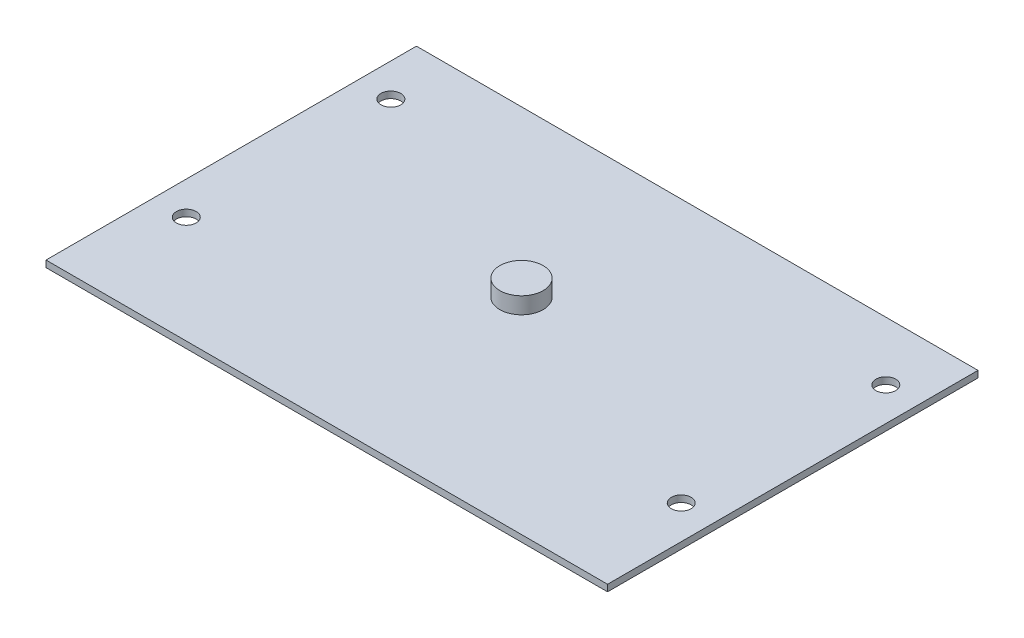
SolidWorks part; units mm, degrees
ref_plane "Front Plane" through (0, 0, 0) normal (0, 0, 1) x (1, 0, 0)
ref_plane "Top Plane" through (0, 0, 0) normal (0, 1, 0) x (1, 0, 0)
ref_plane "Right Plane" through (0, 0, 0) normal (1, 0, 0) x (0, 0, -1)
sketch "Sketch1" plane through (0, 0, 0) normal (0, 1, 0) x (1, 0, 0)
  line L1 (0, 0) -> (85.09, 0)
  line L2 (0, 0) -> (0, 56.134)
  line L3 (0, 56.134) -> (85.09, 56.134)
  line L4 (85.09, 0) -> (85.09, 56.134)
  circle A0 centre (5.01, 47.244) radius 1.5
  circle A1 centre (80.01, 47.244) radius 1.5
  circle A2 centre (5.01, 16.244) radius 1.5
  circle A3 centre (80.01, 16.244) radius 1.5
  dimension "D3" = 3
  dimension "D4" = 3
  dimension "D5" = 3
  dimension "D6" = 3
  dimension "D1" = 85.09
  dimension "D2" = 56.134
  dimension "D7" = 75
  dimension "D8" = 31
  dimension "D9" = 5.08
  dimension "D10" = 8.89
extrude "Boss-Extrude1" add sketch "Sketch1" along normal blind 1
sketch "Sketch2" plane through (0, 1, 0) normal (0, 1, 0) x (1, 0, 0)
  circle A0 centre (40.8981, 31.1545) radius 3.2832
extrude "Boss-Extrude2" add sketch "Sketch2" along normal blind 2.5
